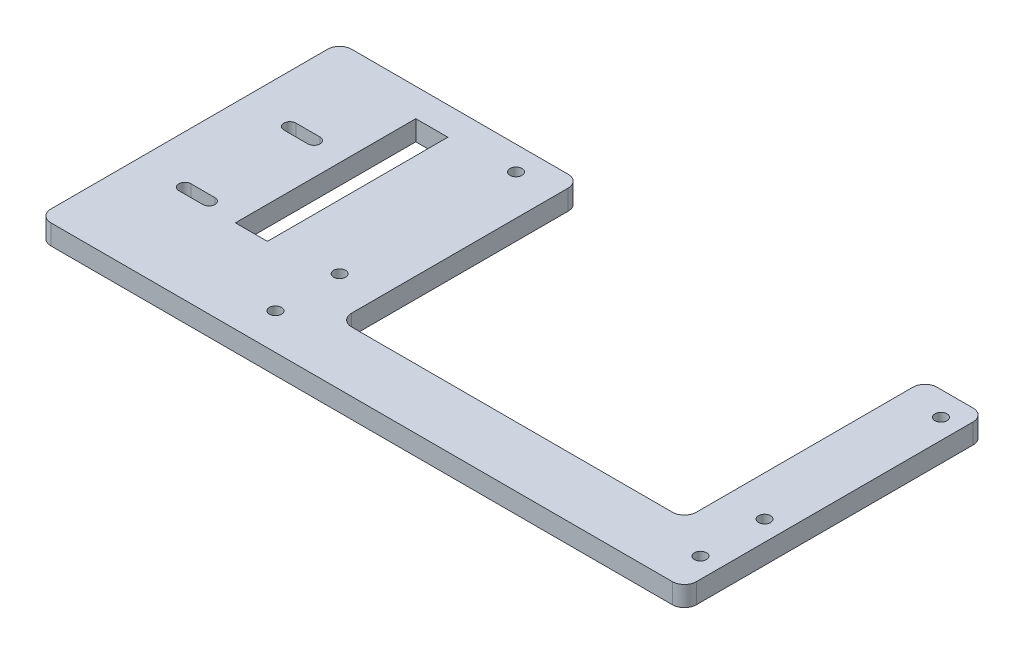
SolidWorks part; units mm, degrees
material "6063-T5"
ref_plane "前视基准面" through (0, 0, 0) normal (0, 0, 1) x (1, 0, 0)
ref_plane "上视基准面" through (0, 0, 0) normal (0, 1, 0) x (1, 0, 0)
ref_plane "右视基准面" through (0, 0, 0) normal (1, 0, 0) x (0, 0, -1)
other "Configuration Table"
sketch "草图1" plane through (0, 0, 0) normal (0, 1, 0) x (1, 0, 0)
  line L0 (0, 0) -> (0, 60)
  line L1 (0, 60) -> (-60, 60)
  line L3 (-60, -15) -> (101, -15)
  line L4 (101, -15) -> (101, 60)
  line L5 (101, 60) -> (86, 60)
  line L6 (86, 60) -> (86, 0)
  line L7 (86, 0) -> (0, 0)
  line L8 (0, 30) -> (59.3, 30) construction
  line L9 (59.3, 30) -> (0, 30) construction
  line L10 (43, 78.0523) -> (43, -12.0435) construction
  line L11 (-60, 60) -> (-60, -15)
  circle A0 centre (-10, 54) radius 1.5
  circle A1 centre (-10, -6) radius 1.5
  circle A2 centre (96, 54) radius 1.5
  circle A3 centre (96, -6) radius 1.5
  circle A4 centre (96, 10) radius 1.5
  circle A5 centre (-10, 10) radius 1.5
  dimension "D10" = 60
  dimension "D18" = 3
  dimension "D19" = 10
  dimension "D20" = 10
  dimension "D1" = 75
  dimension "D3" = 15
  dimension "D4" = 15
  dimension "D5" = 75
  dimension "D6" = 86
  dimension "D7" = 6
  dimension "D9" = 6
  dimension "D12" = 44
  dimension "D13" = 9
  dimension "D14" = 9
  dimension "D15" = 25
extrude "凸台-拉伸1" add sketch "草图1" along normal blind 5
sketch "草图11" plane through (0, 5, 0) normal (0, 1, 0) x (1, 0, 0)
  line L0 (0, 60) -> (-60, 60) construction
  line L1 (-34, 53) -> (-26, 53)
  line L2 (-34, 53) -> (-34, 8)
  line L3 (-34, 8) -> (-26, 8)
  line L4 (-26, 53) -> (-26, 8)
  line L5 (-60, 60) -> (-60, -15) construction
  dimension "D1" = 45
  dimension "D2" = 7
  dimension "D3" = 26
  dimension "D4" = 8
extrude "切除-拉伸6" cut sketch "草图11" against normal through all
fillet "圆角1" radius 3 8 edges at (101, 2.5, 15) (-60, 2.5, 15) (0, 2.5, 0) (86, 2.5, 0) (101, 2.5, -60) (86, 2.5, -60) (0, 2.5, -60) (-60, 2.5, -60)
sketch "草图12" plane through (0, 5, 0) normal (0, 1, 0) x (1, 0, 0)
  line L0 (-48, 35.6) -> (-42, 35.6) construction
  line L1 (-48, 37.1) -> (-42, 37.1)
  line L2 (-48, 34.1) -> (-42, 34.1)
  line L4 (-60, 57) -> (-60, -12) construction
  line L5 (-60, 22.5) -> (-11.9725, 22.5) construction
  line L6 (-48, 9.4) -> (-42, 9.4) construction
  line L7 (-48, 7.9) -> (-42, 7.9)
  line L8 (-48, 10.9) -> (-42, 10.9)
  arc A0 (-48, 37.1) -> (-48, 34.1) centre (-48, 35.6) ccw
  arc A1 (-42, 34.1) -> (-42, 37.1) centre (-42, 35.6) ccw
  arc A2 (-48, 7.9) -> (-48, 10.9) centre (-48, 9.4) cw
  arc A3 (-42, 10.9) -> (-42, 7.9) centre (-42, 9.4) cw
  point P2 (-45, 35.6)
  point P11 (-45, 9.4)
  dimension "D1" = 3
  dimension "D2" = 11.6
  dimension "D3" = 6
  dimension "D4" = 15
extrude "切除-拉伸7" cut sketch "草图12" against normal through all
ref_plane "基准面1" through (43, 0, 0) normal (-1, 0, 0) x (0, 0, 1)
